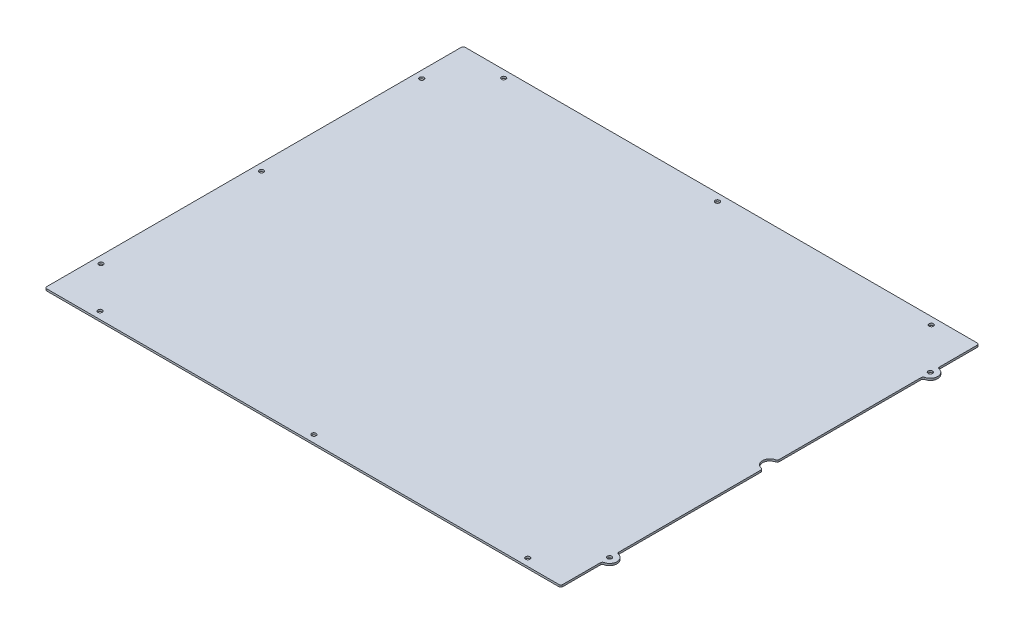
SolidWorks part; units mm, degrees
ref_plane "Front Plane" through (0, 0, 0) normal (0, 0, 1) x (1, 0, 0)
ref_plane "Top Plane" through (0, 0, 0) normal (0, 1, 0) x (1, 0, 0)
ref_plane "Right Plane" through (0, 0, 0) normal (1, 0, 0) x (0, 0, -1)
sketch "Sketch1" plane through (0, 0, 0) normal (0, 1, 0) x (1, 0, 0)
  line L0 (332.232, 273.304) -> (332.232, 219.202) construction
  line L1 (-341.884, -273.304) -> (332.232, -273.304)
  line L2 (-341.884, -273.304) -> (-341.884, 273.304)
  line L3 (-341.884, 273.304) -> (332.232, 273.304)
  line L4 (332.232, -219.202) -> (332.232, -273.304) construction
  line L5 (-341.884, -273.304) -> (341.884, 273.304) construction
  line L6 (-341.884, 273.304) -> (341.884, -273.304) construction
  line L7 (332.232, 273.304) -> (332.232, 219.202)
  line L8 (332.232, 199.898) -> (332.232, 9.652) construction
  line L9 (332.232, 199.898) -> (332.232, 9.652)
  line L10 (332.232, -9.652) -> (332.232, -199.898) construction
  line L11 (332.232, -9.652) -> (332.232, -199.898)
  line L12 (332.232, -219.202) -> (332.232, -273.304)
  arc A0 (332.232, 199.898) -> (332.232, 219.202) centre (332.232, 209.55) ccw
  arc A1 (332.232, -219.202) -> (332.232, -199.898) centre (332.232, -209.55) ccw
  arc A2 (332.232, 9.652) -> (332.232, -9.652) centre (332.232, 0) ccw
  point P0 (0, 0)
  dimension "D4" = 63.754
  dimension "D5" = 19.304
  dimension "D7" = 63.754
  dimension "D1" = 683.768
  dimension "D2" = 546.608
extrude "Boss-Extrude1" add sketch "Sketch1" along normal blind 2.54
hole_wizard "#1 (0.228) Diameter Hole1" positions "Sketch2" profile "Sketch3" hole size "#1" standard "ANSI Inch" end condition through all
sketch "Sketch2" plane through (0, 2.54, 0) normal (0, 1, 0) x (1, 0, 0)
  point P0 (332.232, 209.55)
  point P3 (332.232, -209.55)
sketch "Sketch3" plane through (332.232, 2.54, -209.55) normal (1, 0, 0) x (0, 0, 1)
  line L0 (0, 0) -> (0, 2.54)
  line L1 (0, 2.54) -> (2.8956, 2.54)
  line L2 (2.8956, 2.54) -> (2.8956, 0)
  line L5 (2.8956, 0) -> (0, 0)
  line L11 (0, -6.35) -> (0, 107.95) construction
  dimension "Thru Hole Dia." = 5.7912
  dimension "Thru Hole Depth" = 2.54
fillet "Fillet1" radius 2.54 10 edges at (332.232, 1.27, 273.304) (332.232, 1.27, 219.202) (332.232, 1.27, 199.898) (332.232, 1.27, 9.652) (332.232, 1.27, -9.652) (332.232, 1.27, -199.898) (332.232, 1.27, -219.202) (332.232, 1.27, -273.304) (-341.884, 1.27, -273.304) (-341.884, 1.27, 273.304)
hole_wizard "#1 (0.228) Diameter Hole2" positions "Sketch4" profile "Sketch5" hole size "#1" standard "ANSI Inch" end condition through all
sketch "Sketch4" plane through (0, 0, 0) normal (0, -1, 0) x (-1, 0, 0)
  point P0 (-279.4, 263.652)
  point P3 (0, 263.652)
  point P6 (279.4, 263.652)
  point P9 (332.232, 209.55)
  point P12 (332.232, 0)
  point P15 (332.232, -209.55)
  point P18 (279.4, -263.652)
  point P21 (0, -263.652)
  point P24 (-279.4, -263.652)
sketch "Sketch5" plane through (279.4, 0, -263.652) normal (1, 0, 0) x (0, 0, -1)
  line L0 (0, 0) -> (0, 2.54)
  line L1 (0, 2.54) -> (2.8956, 2.54)
  line L2 (2.8956, 2.54) -> (2.8956, 0)
  line L5 (2.8956, 0) -> (0, 0)
  line L11 (0, -6.35) -> (0, 107.95) construction
  dimension "Thru Hole Dia." = 5.7912
  dimension "Thru Hole Depth" = 2.54
